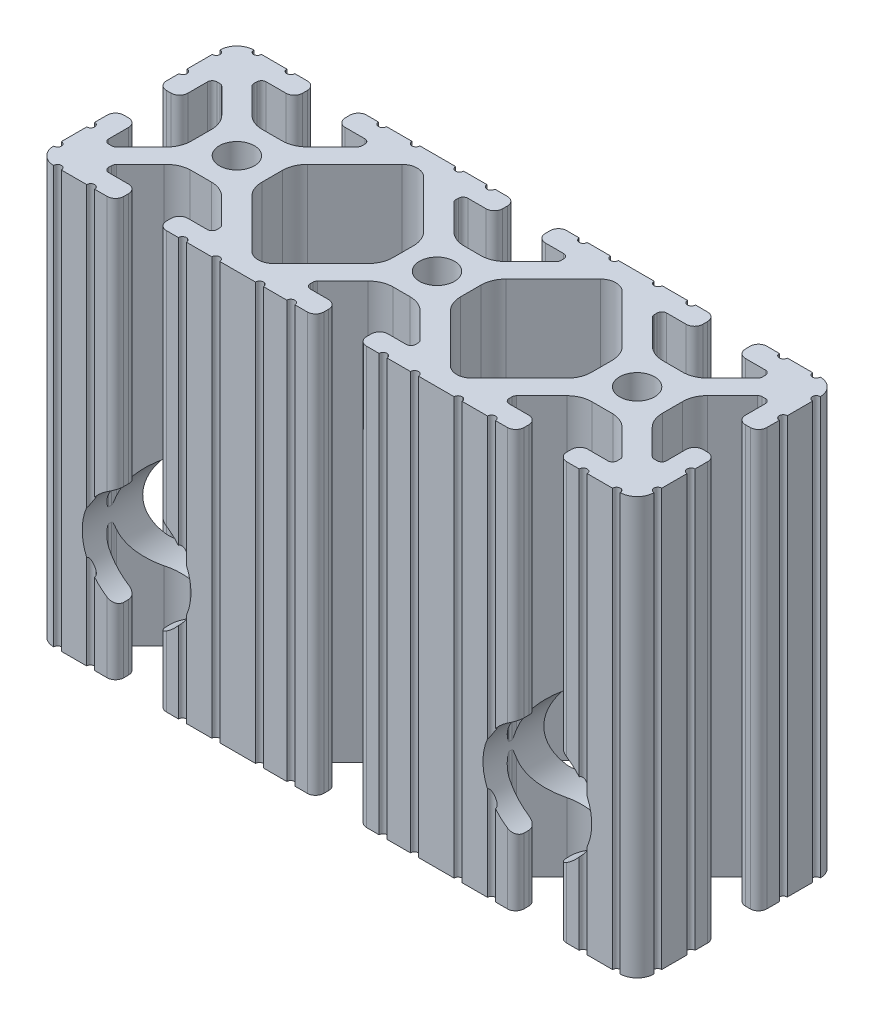
SolidWorks part; units mm, degrees
material "6061-T6 (SS)"
ref_plane "Front" through (0, 0, 0) normal (0, 0, 1) x (1, 0, 0)
ref_plane "Top" through (0, 0, 0) normal (0, 1, 0) x (1, 0, 0)
ref_plane "Right" through (0, 0, 0) normal (1, 0, 0) x (0, 0, -1)
sketch "Sketch1" plane through (0, 0, 0) normal (0, 0, 1) x (1, 0, 0)
  line L0 (0, -39.6875) -> (0, 39.6875)
  dimension "D1" = 79.375
other "15 1545 PROFILE(1)"
ref_plane "Plane1" through (0, -39.6875, 0) normal (0, 1, 0) x (0, 0, 1)
sketch "Sketch14" plane through (0, -39.6875, 0) normal (0, 1, 0) x (0, 0, 1)
  line L1 (19.05, 57.15) -> (-19.05, 57.15) construction
  line L2 (19.05, 57.15) -> (19.05, 19.05) construction
  line L3 (19.05, 19.05) -> (-19.05, 19.05) construction
  line L4 (-19.05, 57.15) -> (-19.05, 19.05) construction
  line L5 (19.05, 57.15) -> (-19.05, 19.05) construction
  line L6 (19.05, 19.05) -> (-19.05, 57.15) construction
  line L7 (19.05, 19.05) -> (-19.05, 19.05) construction
  line L8 (19.05, 19.05) -> (19.05, -19.05) construction
  line L9 (19.05, -19.05) -> (-19.05, -19.05) construction
  line L10 (-19.05, 19.05) -> (-19.05, -19.05) construction
  line L11 (19.05, 19.05) -> (-19.05, -19.05) construction
  line L12 (19.05, -19.05) -> (-19.05, 19.05) construction
  line L13 (-14.2815, 16.8269) -> (-5.2928, 7.8382)
  line L14 (-5.2928, 29.9713) -> (-14.2815, 20.9826)
  line L15 (1.9341, 31.3625) -> (-1.9341, 31.3625)
  line L16 (14.2815, 20.9826) -> (5.2928, 29.9713)
  line L17 (5.2928, 7.8382) -> (14.2815, 16.8269)
  line L18 (-1.9341, 6.447) -> (1.9341, 6.447)
  line L19 (19.05, -57.15) -> (-19.05, -57.15) construction
  line L20 (19.05, -57.15) -> (19.05, -19.05) construction
  line L21 (19.05, -19.05) -> (-19.05, -19.05) construction
  line L22 (-19.05, -57.15) -> (-19.05, -19.05) construction
  line L23 (19.05, -57.15) -> (-19.05, -19.05) construction
  line L24 (19.05, -19.05) -> (-19.05, -57.15) construction
  line L26 (1.9341, -6.447) -> (-1.9341, -6.447)
  line L27 (14.2815, -16.8269) -> (5.2928, -7.8382)
  line L28 (5.2928, -29.9713) -> (14.2815, -20.9826)
  line L29 (-1.9341, -31.3625) -> (1.9341, -31.3625)
  line L30 (-14.2815, -20.9826) -> (-5.2928, -29.9713)
  line L31 (-5.2928, -7.8382) -> (-14.2815, -16.8269)
  line L216 (-14.986, -9.1305) -> (-14.986, -5.6388)
  line L217 (-16.5608, -4.064) -> (-17.4752, -4.064)
  line L218 (-19.05, -5.6388) -> (-19.05, -8.0238)
  line L219 (-19.05, -9.5478) -> (-19.05, -13.9845)
  line L220 (-19.05, -15.5085) -> (-19.05, -22.301)
  line L221 (-19.05, -23.825) -> (-19.05, -28.6534)
  line L222 (-19.05, -30.1774) -> (-19.05, -32.4612)
  line L223 (-17.4752, -34.036) -> (-16.5608, -34.036)
  line L224 (-14.986, -32.4612) -> (-14.986, -28.7209)
  line L225 (-14.097, -27.8319) -> (-13.5478, -27.8319)
  line L226 (-12.9192, -28.0922) -> (-8.1476, -32.8638)
  line L227 (-6.7564, -36.2224) -> (-6.7564, -40.2439)
  line L228 (-8.3762, -43.6025) -> (-12.9192, -48.1455)
  line L229 (-13.5478, -48.4059) -> (-14.097, -48.4059)
  line L230 (-14.986, -47.5169) -> (-14.986, -43.7388)
  line L231 (-16.5608, -42.164) -> (-17.4752, -42.164)
  line L232 (-19.05, -43.7388) -> (-19.05, -46.1257)
  line L233 (-19.05, -47.6497) -> (-19.05, -52.4761)
  line L234 (-14.3761, -57.15) -> (-9.5497, -57.15)
  line L235 (-8.0257, -57.15) -> (-5.6388, -57.15)
  line L236 (-4.064, -55.5752) -> (-4.064, -54.6608)
  line L237 (-5.6388, -53.086) -> (-9.4169, -53.086)
  line L238 (-10.287, -52.2159) -> (-10.287, -51.6289)
  line L239 (-10.0266, -51.0003) -> (-5.2739, -46.2476)
  line L240 (-1.9153, -44.8564) -> (1.9153, -44.8564)
  line L241 (5.2739, -46.2476) -> (10.0266, -51.0003)
  line L242 (10.287, -51.6289) -> (10.287, -52.2159)
  line L243 (9.4169, -53.086) -> (5.6388, -53.086)
  line L244 (4.064, -54.6608) -> (4.064, -55.5752)
  line L245 (5.6388, -57.15) -> (8.0257, -57.15)
  line L246 (9.5497, -57.15) -> (14.3761, -57.15)
  line L247 (19.05, -52.4761) -> (19.05, -47.6497)
  line L248 (19.05, -46.1257) -> (19.05, -43.7388)
  line L249 (17.4752, -42.164) -> (16.5608, -42.164)
  line L250 (14.986, -43.7388) -> (14.986, -47.5169)
  line L251 (14.097, -48.4059) -> (13.5478, -48.4059)
  line L252 (12.9192, -48.1455) -> (8.3762, -43.6025)
  line L253 (6.7564, -40.2439) -> (6.7564, -36.2224)
  line L254 (8.1476, -32.8638) -> (12.9192, -28.0922)
  line L255 (13.5478, -27.8319) -> (14.097, -27.8319)
  line L256 (14.986, -28.7209) -> (14.986, -32.4612)
  line L257 (16.5608, -34.036) -> (17.4752, -34.036)
  line L258 (19.05, -32.4612) -> (19.05, -30.1774)
  line L259 (19.05, -28.6534) -> (19.05, -23.825)
  line L260 (19.05, -22.301) -> (19.05, -15.5085)
  line L261 (19.05, -13.9845) -> (19.05, -9.5478)
  line L262 (19.05, -8.0238) -> (19.05, -5.6388)
  line L263 (17.4752, -4.064) -> (16.5608, -4.064)
  line L264 (14.986, -5.6388) -> (14.986, -9.1305)
  line L265 (14.097, -10.0195) -> (13.5896, -10.0195)
  line L266 (12.961, -9.7591) -> (8.1476, -4.9457)
  line L267 (6.7564, -1.5871) -> (6.7564, 1.5871)
  line L268 (8.1476, 4.9457) -> (12.961, 9.7591)
  line L269 (13.5896, 10.0195) -> (14.097, 10.0195)
  line L270 (14.986, 9.1305) -> (14.986, 5.6388)
  line L271 (16.5608, 4.064) -> (17.4752, 4.064)
  line L272 (19.05, 5.6388) -> (19.05, 8.0238)
  line L273 (19.05, 9.5478) -> (19.05, 13.9845)
  line L274 (19.05, 15.5085) -> (19.05, 22.301)
  line L275 (19.05, 23.825) -> (19.05, 28.6534)
  line L276 (19.05, 30.1774) -> (19.05, 32.4612)
  line L277 (17.4752, 34.036) -> (16.5608, 34.036)
  line L278 (14.986, 32.4612) -> (14.986, 28.7209)
  line L279 (14.097, 27.8319) -> (13.5478, 27.8319)
  line L280 (12.9192, 28.0922) -> (8.1476, 32.8638)
  line L281 (6.7564, 36.2224) -> (6.7564, 40.2439)
  line L282 (8.3762, 43.6025) -> (12.9192, 48.1455)
  line L283 (13.5478, 48.4059) -> (14.097, 48.4059)
  line L284 (14.986, 47.5169) -> (14.986, 43.7388)
  line L285 (16.5608, 42.164) -> (17.4752, 42.164)
  line L286 (19.05, 43.7388) -> (19.05, 46.1257)
  line L287 (19.05, 47.6497) -> (19.05, 52.4761)
  line L288 (14.3761, 57.15) -> (9.5497, 57.15)
  line L289 (8.0257, 57.15) -> (5.6388, 57.15)
  line L290 (4.064, 55.5752) -> (4.064, 54.6608)
  line L291 (5.6388, 53.086) -> (9.4169, 53.086)
  line L292 (10.287, 52.2159) -> (10.287, 51.6289)
  line L293 (10.0266, 51.0003) -> (5.2739, 46.2476)
  line L294 (1.9153, 44.8564) -> (-1.9153, 44.8564)
  line L295 (-5.2739, 46.2476) -> (-10.0266, 51.0003)
  line L296 (-10.287, 51.6289) -> (-10.287, 52.2159)
  line L297 (-9.4169, 53.086) -> (-5.6388, 53.086)
  line L298 (-4.064, 54.6608) -> (-4.064, 55.5752)
  line L299 (-5.6388, 57.15) -> (-8.0257, 57.15)
  line L300 (-9.5497, 57.15) -> (-14.3761, 57.15)
  line L301 (-19.05, 52.4761) -> (-19.05, 47.6497)
  line L302 (-19.05, 46.1257) -> (-19.05, 43.7388)
  line L303 (-17.4752, 42.164) -> (-16.5608, 42.164)
  line L304 (-14.986, 43.7388) -> (-14.986, 47.5169)
  line L305 (-14.097, 48.4059) -> (-13.5478, 48.4059)
  line L306 (-12.9192, 48.1455) -> (-8.3762, 43.6025)
  line L307 (-6.7564, 40.2439) -> (-6.7564, 36.2224)
  line L308 (-8.1476, 32.8638) -> (-12.9192, 28.0922)
  line L309 (-13.5478, 27.8319) -> (-14.097, 27.8319)
  line L310 (-14.986, 28.7209) -> (-14.986, 32.4612)
  line L311 (-16.5608, 34.036) -> (-17.4752, 34.036)
  line L312 (-19.05, 32.4612) -> (-19.05, 30.1774)
  line L313 (-19.05, 28.6534) -> (-19.05, 23.825)
  line L314 (-19.05, 22.301) -> (-19.05, 15.5085)
  line L315 (-19.05, 13.9845) -> (-19.05, 9.5478)
  line L316 (-19.05, 8.0238) -> (-19.05, 5.6388)
  line L317 (-17.4752, 4.064) -> (-16.5608, 4.064)
  line L318 (-14.986, 5.6388) -> (-14.986, 9.1305)
  line L319 (-14.097, 10.0195) -> (-13.5896, 10.0195)
  line L320 (-12.961, 9.7591) -> (-8.1476, 4.9457)
  line L321 (-6.7564, 1.5871) -> (-6.7564, -1.5871)
  line L322 (-8.1476, -4.9457) -> (-12.961, -9.7591)
  line L323 (-13.5896, -10.0195) -> (-14.097, -10.0195)
  circle A1 centre (0, 38.1) radius 3.3274
  circle A3 centre (0, 0) radius 3.3274
  circle A5 centre (0, -38.1) radius 3.3274
  arc A14 (-5.2928, 7.8382) -> (-1.9341, 6.447) centre (-1.9341, 11.1968) ccw
  arc A15 (-14.2815, 20.9826) -> (-14.2815, 16.8269) centre (-12.2036, 18.9048) ccw
  arc A16 (-1.9341, 31.3625) -> (-5.2928, 29.9713) centre (-1.9341, 26.6127) ccw
  arc A17 (5.2928, 29.9713) -> (1.9341, 31.3625) centre (1.9341, 26.6127) ccw
  arc A18 (14.2815, 16.8269) -> (14.2815, 20.9826) centre (12.2036, 18.9048) ccw
  arc A19 (1.9341, 6.447) -> (5.2928, 7.8382) centre (1.9341, 11.1968) ccw
  arc A28 (-1.9341, -6.447) -> (-5.2928, -7.8382) centre (-1.9341, -11.1968) ccw
  arc A29 (5.2928, -7.8382) -> (1.9341, -6.447) centre (1.9341, -11.1968) ccw
  arc A30 (14.2815, -20.9826) -> (14.2815, -16.8269) centre (12.2036, -18.9048) ccw
  arc A31 (1.9341, -31.3625) -> (5.2928, -29.9713) centre (1.9341, -26.6127) ccw
  arc A32 (-5.2928, -29.9713) -> (-1.9341, -31.3625) centre (-1.9341, -26.6127) ccw
  arc A33 (-14.2815, -16.8269) -> (-14.2815, -20.9826) centre (-12.2036, -18.9048) ccw
  arc A232 (-14.986, -9.1305) -> (-14.097, -10.0195) centre (-14.097, -9.1305) ccw
  arc A233 (-14.986, -5.6388) -> (-16.5608, -4.064) centre (-16.5608, -5.6388) ccw
  arc A234 (-17.4752, -4.064) -> (-19.05, -5.6388) centre (-17.4752, -5.6388) ccw
  arc A235 (-19.05, -9.5478) -> (-19.05, -8.0238) centre (-19.05, -8.7858) ccw
  arc A236 (-19.05, -15.5085) -> (-19.05, -13.9845) centre (-19.05, -14.7465) ccw
  arc A237 (-19.05, -23.825) -> (-19.05, -22.301) centre (-19.05, -23.063) ccw
  arc A238 (-19.05, -30.1774) -> (-19.05, -28.6534) centre (-19.05, -29.4154) ccw
  arc A239 (-19.05, -32.4612) -> (-17.4752, -34.036) centre (-17.4752, -32.4612) ccw
  arc A240 (-16.5608, -34.036) -> (-14.986, -32.4612) centre (-16.5608, -32.4612) ccw
  arc A241 (-14.097, -27.8319) -> (-14.986, -28.7209) centre (-14.097, -28.7209) ccw
  arc A242 (-12.9192, -28.0922) -> (-13.5478, -27.8319) centre (-13.5478, -28.7209) ccw
  arc A243 (-6.7564, -36.2224) -> (-8.1476, -32.8638) centre (-11.5062, -36.2224) ccw
  arc A244 (-8.3762, -43.6025) -> (-6.7564, -40.2439) centre (-11.5012, -40.0255) ccw
  arc A245 (-13.5478, -48.4059) -> (-12.9192, -48.1455) centre (-13.5478, -47.5169) ccw
  arc A246 (-14.986, -47.5169) -> (-14.097, -48.4059) centre (-14.097, -47.5169) ccw
  arc A247 (-14.986, -43.7388) -> (-16.5608, -42.164) centre (-16.5608, -43.7388) ccw
  arc A248 (-17.4752, -42.164) -> (-19.05, -43.7388) centre (-17.4752, -43.7388) ccw
  arc A249 (-19.05, -47.6497) -> (-19.05, -46.1257) centre (-19.05, -46.8877) ccw
  arc A250 (-19.0499, -53.9265) -> (-19.05, -52.4761) centre (-19.0141, -53.2013) ccw
  arc A251 (-19.0499, -53.9265) -> (-15.8265, -57.1499) centre (-15.8046, -53.9046) ccw
  arc A252 (-14.3761, -57.15) -> (-15.8265, -57.1499) centre (-15.1013, -57.1141) ccw
  arc A253 (-8.0257, -57.15) -> (-9.5497, -57.15) centre (-8.7877, -57.15) ccw
  arc A254 (-5.6388, -57.15) -> (-4.064, -55.5752) centre (-5.6388, -55.5752) ccw
  arc A255 (-4.064, -54.6608) -> (-5.6388, -53.086) centre (-5.6388, -54.6608) ccw
  arc A256 (-10.287, -52.2159) -> (-9.4169, -53.086) centre (-9.4169, -52.2159) ccw
  arc A257 (-10.0266, -51.0003) -> (-10.287, -51.6289) centre (-9.398, -51.6289) ccw
  arc A258 (-1.9153, -44.8564) -> (-5.2739, -46.2476) centre (-1.9153, -49.6062) ccw
  arc A259 (5.2739, -46.2476) -> (1.9153, -44.8564) centre (1.9153, -49.6062) ccw
  arc A260 (10.287, -51.6289) -> (10.0266, -51.0003) centre (9.398, -51.6289) ccw
  arc A261 (9.4169, -53.086) -> (10.287, -52.2159) centre (9.4169, -52.2159) ccw
  arc A262 (5.6388, -53.086) -> (4.064, -54.6608) centre (5.6388, -54.6608) ccw
  arc A263 (4.064, -55.5752) -> (5.6388, -57.15) centre (5.6388, -55.5752) ccw
  arc A264 (9.5497, -57.15) -> (8.0257, -57.15) centre (8.7877, -57.15) ccw
  arc A265 (15.8265, -57.1499) -> (14.3761, -57.15) centre (15.1013, -57.1141) ccw
  arc A266 (15.8265, -57.1499) -> (19.0499, -53.9265) centre (15.8046, -53.9046) ccw
  arc A267 (19.05, -52.4761) -> (19.0499, -53.9265) centre (19.0141, -53.2013) ccw
  arc A268 (19.05, -46.1257) -> (19.05, -47.6497) centre (19.05, -46.8877) ccw
  arc A269 (19.05, -43.7388) -> (17.4752, -42.164) centre (17.4752, -43.7388) ccw
  arc A270 (16.5608, -42.164) -> (14.986, -43.7388) centre (16.5608, -43.7388) ccw
  arc A271 (14.097, -48.4059) -> (14.986, -47.5169) centre (14.097, -47.5169) ccw
  arc A272 (12.9192, -48.1455) -> (13.5478, -48.4059) centre (13.5478, -47.5169) ccw
  arc A273 (6.7564, -40.2439) -> (8.3762, -43.6025) centre (11.5012, -40.0255) ccw
  arc A274 (8.1476, -32.8638) -> (6.7564, -36.2224) centre (11.5062, -36.2224) ccw
  arc A275 (13.5478, -27.8319) -> (12.9192, -28.0922) centre (13.5478, -28.7209) ccw
  arc A276 (14.986, -28.7209) -> (14.097, -27.8319) centre (14.097, -28.7209) ccw
  arc A277 (14.986, -32.4612) -> (16.5608, -34.036) centre (16.5608, -32.4612) ccw
  arc A278 (17.4752, -34.036) -> (19.05, -32.4612) centre (17.4752, -32.4612) ccw
  arc A279 (19.05, -28.6534) -> (19.05, -30.1774) centre (19.05, -29.4154) ccw
  arc A280 (19.05, -22.301) -> (19.05, -23.825) centre (19.05, -23.063) ccw
  arc A281 (19.05, -13.9845) -> (19.05, -15.5085) centre (19.05, -14.7465) ccw
  arc A282 (19.05, -8.0238) -> (19.05, -9.5478) centre (19.05, -8.7858) ccw
  arc A283 (19.05, -5.6388) -> (17.4752, -4.064) centre (17.4752, -5.6388) ccw
  arc A284 (16.5608, -4.064) -> (14.986, -5.6388) centre (16.5608, -5.6388) ccw
  arc A285 (14.097, -10.0195) -> (14.986, -9.1305) centre (14.097, -9.1305) ccw
  arc A286 (12.961, -9.7591) -> (13.5896, -10.0195) centre (13.5896, -9.1305) ccw
  arc A287 (6.7564, -1.5871) -> (8.1476, -4.9457) centre (11.5062, -1.5871) ccw
  arc A288 (8.1476, 4.9457) -> (6.7564, 1.5871) centre (11.5062, 1.5871) ccw
  arc A289 (13.5896, 10.0195) -> (12.961, 9.7591) centre (13.5896, 9.1305) ccw
  arc A290 (14.986, 9.1305) -> (14.097, 10.0195) centre (14.097, 9.1305) ccw
  arc A291 (14.986, 5.6388) -> (16.5608, 4.064) centre (16.5608, 5.6388) ccw
  arc A292 (17.4752, 4.064) -> (19.05, 5.6388) centre (17.4752, 5.6388) ccw
  arc A293 (19.05, 9.5478) -> (19.05, 8.0238) centre (19.05, 8.7858) ccw
  arc A294 (19.05, 15.5085) -> (19.05, 13.9845) centre (19.05, 14.7465) ccw
  arc A295 (19.05, 23.825) -> (19.05, 22.301) centre (19.05, 23.063) ccw
  arc A296 (19.05, 30.1774) -> (19.05, 28.6534) centre (19.05, 29.4154) ccw
  arc A297 (19.05, 32.4612) -> (17.4752, 34.036) centre (17.4752, 32.4612) ccw
  arc A298 (16.5608, 34.036) -> (14.986, 32.4612) centre (16.5608, 32.4612) ccw
  arc A299 (14.097, 27.8319) -> (14.986, 28.7209) centre (14.097, 28.7209) ccw
  arc A300 (12.9192, 28.0922) -> (13.5478, 27.8319) centre (13.5478, 28.7209) ccw
  arc A301 (6.7564, 36.2224) -> (8.1476, 32.8638) centre (11.5062, 36.2224) ccw
  arc A302 (8.3762, 43.6025) -> (6.7564, 40.2439) centre (11.5012, 40.0255) ccw
  arc A303 (13.5478, 48.4059) -> (12.9192, 48.1455) centre (13.5478, 47.5169) ccw
  arc A304 (14.986, 47.5169) -> (14.097, 48.4059) centre (14.097, 47.5169) ccw
  arc A305 (14.986, 43.7388) -> (16.5608, 42.164) centre (16.5608, 43.7388) ccw
  arc A306 (17.4752, 42.164) -> (19.05, 43.7388) centre (17.4752, 43.7388) ccw
  arc A307 (19.05, 47.6497) -> (19.05, 46.1257) centre (19.05, 46.8877) ccw
  arc A308 (19.0499, 53.9265) -> (19.05, 52.4761) centre (19.0141, 53.2013) ccw
  arc A309 (19.0499, 53.9265) -> (15.8265, 57.1499) centre (15.8046, 53.9046) ccw
  arc A310 (14.3761, 57.15) -> (15.8265, 57.1499) centre (15.1013, 57.1141) ccw
  arc A311 (8.0257, 57.15) -> (9.5497, 57.15) centre (8.7877, 57.15) ccw
  arc A312 (5.6388, 57.15) -> (4.064, 55.5752) centre (5.6388, 55.5752) ccw
  arc A313 (4.064, 54.6608) -> (5.6388, 53.086) centre (5.6388, 54.6608) ccw
  arc A314 (10.287, 52.2159) -> (9.4169, 53.086) centre (9.4169, 52.2159) ccw
  arc A315 (10.0266, 51.0003) -> (10.287, 51.6289) centre (9.398, 51.6289) ccw
  arc A316 (1.9153, 44.8564) -> (5.2739, 46.2476) centre (1.9153, 49.6062) ccw
  arc A317 (-5.2739, 46.2476) -> (-1.9153, 44.8564) centre (-1.9153, 49.6062) ccw
  arc A318 (-10.287, 51.6289) -> (-10.0266, 51.0003) centre (-9.398, 51.6289) ccw
  arc A319 (-9.4169, 53.086) -> (-10.287, 52.2159) centre (-9.4169, 52.2159) ccw
  arc A320 (-5.6388, 53.086) -> (-4.064, 54.6608) centre (-5.6388, 54.6608) ccw
  arc A321 (-4.064, 55.5752) -> (-5.6388, 57.15) centre (-5.6388, 55.5752) ccw
  arc A322 (-9.5497, 57.15) -> (-8.0257, 57.15) centre (-8.7877, 57.15) ccw
  arc A323 (-15.8265, 57.1499) -> (-14.3761, 57.15) centre (-15.1013, 57.1141) ccw
  arc A324 (-15.8265, 57.1499) -> (-19.0499, 53.9265) centre (-15.8046, 53.9046) ccw
  arc A325 (-19.05, 52.4761) -> (-19.0499, 53.9265) centre (-19.0141, 53.2013) ccw
  arc A326 (-19.05, 46.1257) -> (-19.05, 47.6497) centre (-19.05, 46.8877) ccw
  arc A327 (-19.05, 43.7388) -> (-17.4752, 42.164) centre (-17.4752, 43.7388) ccw
  arc A328 (-16.5608, 42.164) -> (-14.986, 43.7388) centre (-16.5608, 43.7388) ccw
  arc A329 (-14.097, 48.4059) -> (-14.986, 47.5169) centre (-14.097, 47.5169) ccw
  arc A330 (-12.9192, 48.1455) -> (-13.5478, 48.4059) centre (-13.5478, 47.5169) ccw
  arc A331 (-6.7564, 40.2439) -> (-8.3762, 43.6025) centre (-11.5012, 40.0255) ccw
  arc A332 (-8.1476, 32.8638) -> (-6.7564, 36.2224) centre (-11.5062, 36.2224) ccw
  arc A333 (-13.5478, 27.8319) -> (-12.9192, 28.0922) centre (-13.5478, 28.7209) ccw
  arc A334 (-14.986, 28.7209) -> (-14.097, 27.8319) centre (-14.097, 28.7209) ccw
  arc A335 (-14.986, 32.4612) -> (-16.5608, 34.036) centre (-16.5608, 32.4612) ccw
  arc A336 (-17.4752, 34.036) -> (-19.05, 32.4612) centre (-17.4752, 32.4612) ccw
  arc A337 (-19.05, 28.6534) -> (-19.05, 30.1774) centre (-19.05, 29.4154) ccw
  arc A338 (-19.05, 22.301) -> (-19.05, 23.825) centre (-19.05, 23.063) ccw
  arc A339 (-19.05, 13.9845) -> (-19.05, 15.5085) centre (-19.05, 14.7465) ccw
  arc A340 (-19.05, 8.0238) -> (-19.05, 9.5478) centre (-19.05, 8.7858) ccw
  arc A341 (-19.05, 5.6388) -> (-17.4752, 4.064) centre (-17.4752, 5.6388) ccw
  arc A342 (-16.5608, 4.064) -> (-14.986, 5.6388) centre (-16.5608, 5.6388) ccw
  arc A343 (-14.097, 10.0195) -> (-14.986, 9.1305) centre (-14.097, 9.1305) ccw
  arc A344 (-12.961, 9.7591) -> (-13.5896, 10.0195) centre (-13.5896, 9.1305) ccw
  arc A345 (-6.7564, 1.5871) -> (-8.1476, 4.9457) centre (-11.5062, 1.5871) ccw
  arc A346 (-8.1476, -4.9457) -> (-6.7564, -1.5871) centre (-11.5062, -1.5871) ccw
  arc A347 (-13.5896, -10.0195) -> (-12.961, -9.7591) centre (-13.5896, -9.1305) ccw
  point P3 (0, 38.1)
  point P101 (0, 0)
  point P151 (0, -38.1)
  point P167 (0, 57.15)
  point P170 (-19.05, 38.1)
  point P173 (-19.05, 0)
  point P175 (-19.05, -38.1)
  point P178 (0, -57.15)
  point P182 (19.05, -38.1)
  point P185 (19.05, 0)
  point P188 (19.05, 38.1)
  point P191 (0, 19.05)
  point P193 (0, -19.05)
  point P196 (19.05, -57.15)
  point P200 (19.05, -19.05)
  point P203 (19.05, 19.05)
  point P206 (19.05, 57.15)
  point P209 (-19.05, 57.15)
  point P212 (-19.05, 19.05)
  point P215 (-19.05, -19.05)
  point P217 (-19.05, -57.15)
  point P220 (0, 0)
  dimension "D1" = 38.1
sketch "Sketch15" plane through (0, 0, 19.05) normal (0, 0, 1) x (1, 0, 0)
  line L0 (30.1774, 39.6875) -> (38.1516, -17.6875) construction
  line L1 (38.1516, -17.6875) -> (46.1257, 39.6875) construction
  line L2 (36.2224, -39.6875) -> (40.2439, -39.6875) construction
  circle A0 centre (38.1516, -17.6875) radius 10.3505
  dimension "D1" = 20.701
  dimension "D2" = 22
extrude "Cut-Extrude1" cut sketch "Sketch15" against normal blind 15.748
mirror "Mirror1" about plane through (0, 0, 0) normal (1, 0, 0) of "Cut-Extrude1"
